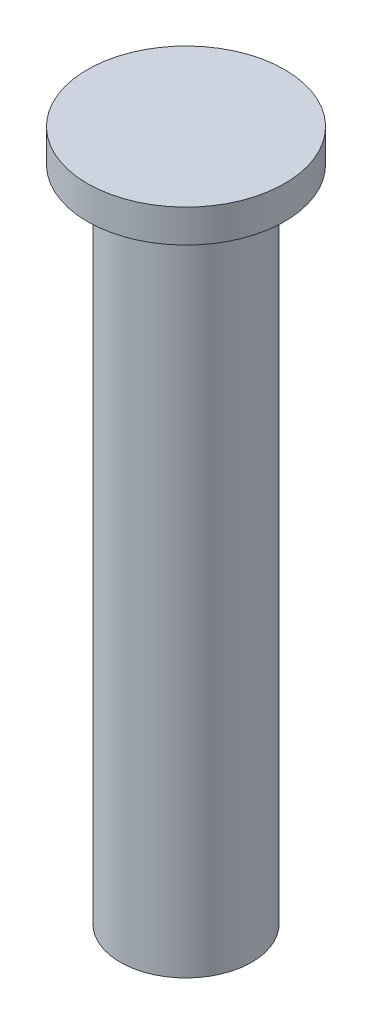
SolidWorks part; units mm, degrees
ref_plane "Front Plane" through (0, 0, 0) normal (0, 0, 1) x (1, 0, 0)
ref_plane "Top Plane" through (0, 0, 0) normal (0, 1, 0) x (1, 0, 0)
ref_plane "Right Plane" through (0, 0, 0) normal (1, 0, 0) x (0, 0, -1)
sketch "Sketch2" plane through (0, 0, 0) normal (0, 0, 1) x (1, 0, 0)
  line L0 (0, 0) -> (0, 1050)
  line L1 (0, 1050) -> (150, 1050)
  line L2 (150, 1050) -> (150, 1000)
  line L3 (150, 1000) -> (100, 1000)
  line L4 (100, 1000) -> (100, 0)
  line L5 (100, 0) -> (0, 0)
  dimension "D1" = 1050
  dimension "D2" = 50
  dimension "D3" = 100
  dimension "D4" = 50
revolve "Revolve1" add sketch "Sketch2" angle 360 about L0
